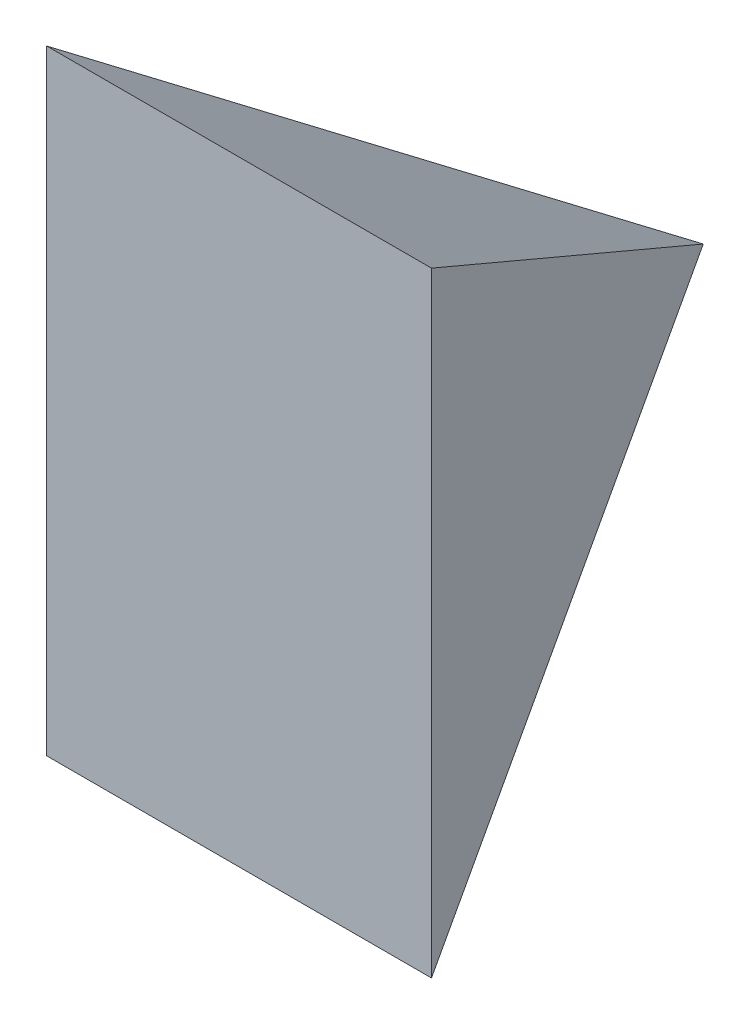
SolidWorks part; units mm, degrees
ref_plane "Plan de face" through (0, 0, 0) normal (0, 0, 1) x (1, 0, 0)
ref_plane "Plan de dessus" through (0, 0, 0) normal (0, 1, 0) x (1, 0, 0)
ref_plane "Plan de droite" through (0, 0, 0) normal (1, 0, 0) x (0, 0, -1)
sketch "Esquisse1" plane through (0, 0, 0) normal (0, 0, 1) x (1, 0, 0)
  point P0 (0, 0)
ref_plane "Plan1" through (0, 0, 450) normal (0, 0, 1) x (1, 0, 0)
sketch "Esquisse2" plane through (0, 0, 450) normal (0, 0, 1) x (1, 0, 0)
  line L1 (-186.5, 298) -> (186.5, 298)
  line L2 (-186.5, 298) -> (-186.5, -298)
  line L3 (-186.5, -298) -> (186.5, -298)
  line L4 (186.5, 298) -> (186.5, -298)
  line L5 (-186.5, 298) -> (186.5, -298) construction
  line L6 (-186.5, -298) -> (186.5, 298) construction
  point P0 (0, 0)
  dimension "D1" = 596
  dimension "D2" = 373
loft "Lissage1" add profiles "Esquisse1", "Esquisse2"
